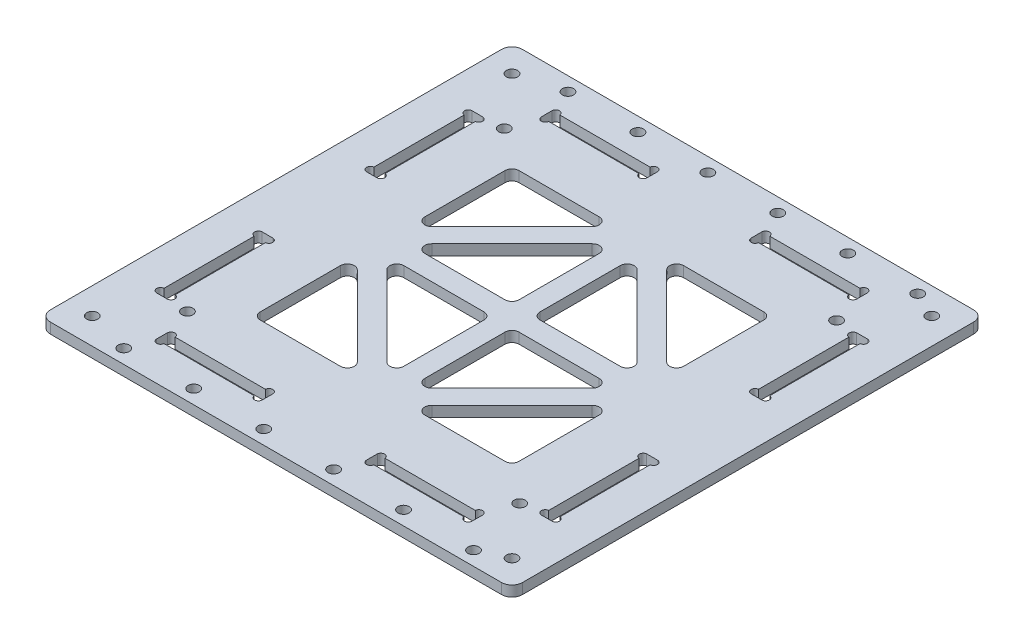
SolidWorks part; units mm, degrees
material "轻木"
ref_plane "Front" through (0, 0, 0) normal (0, 0, 1) x (1, 0, 0)
ref_plane "Top" through (0, 0, 0) normal (0, 1, 0) x (1, 0, 0)
ref_plane "Right" through (0, 0, 0) normal (1, 0, 0) x (0, 0, -1)
sketch "草图1" plane through (0, 0, 0) normal (0, 1, 0) x (1, 0, 0)
  line L1 (-67.5, 67.5) -> (67.5, 67.5)
  line L2 (-67.5, 67.5) -> (-67.5, -67.5)
  line L3 (-67.5, -67.5) -> (67.5, -67.5)
  line L4 (67.5, 67.5) -> (67.5, -67.5)
  line L5 (0, -67.5) -> (0, 67.5) construction
  line L6 (-67.5, 0) -> (67.5, 0) construction
  line L7 (-47.5, -45.3) -> (47.5, -45.3) construction
  line L8 (-47.5, -45.3) -> (-47.5, 45.3) construction
  line L9 (-47.5, 45.3) -> (47.5, 45.3) construction
  line L10 (47.5, -45.3) -> (47.5, 45.3) construction
  line L11 (0, 45.3) -> (0, -45.3) construction
  line L12 (-47.5, 0) -> (47.5, 0) construction
  circle A0 centre (-47.5, 45.3) radius 1.6
  circle A1 centre (47.5, 45.3) radius 1.6
  circle A2 centre (47.5, -45.3) radius 1.6
  circle A3 centre (-47.5, -45.3) radius 1.6
  point P0 (0, 0)
  point P4 (0, 0)
  point P95 (0.9739, 0)
  dimension "D7" = 3.2
  dimension "D1" = 135
  dimension "D2" = 135
  dimension "D3" = 95
  dimension "D4" = 90.6
extrude "凸台-拉伸1" add sketch "草图1" along normal blind 3
sketch "草图2" plane through (0, 3, 0) normal (0, 1, 0) x (1, 0, 0)
  line L0 (-67.5, 55) -> (67.5, 55) construction
  line L1 (-67.5, 67.5) -> (-67.5, -67.5) construction
  line L2 (67.5, -67.5) -> (67.5, 67.5) construction
  line L3 (-67.5, -55) -> (67.5, -55) construction
  line L4 (-45.1, 53.4) -> (-14.9, 53.4)
  line L5 (0, 55) -> (0, -55) construction
  line L6 (-14.9, 53.4) -> (-14.9, 56.6)
  line L7 (-45, 53.5) -> (-15, 53.5)
  line L8 (-45, 53.5) -> (-45, 56.5)
  line L9 (-45, 56.5) -> (-15, 56.5)
  line L10 (-15, 53.5) -> (-15, 56.5)
  line L11 (-30, 56.5) -> (-30, 53.5) construction
  line L12 (-45, 55) -> (-15, 55) construction
  line L13 (-45.1, 56.6) -> (-14.9, 56.6)
  line L14 (-45.1, 53.4) -> (-45.1, 56.6)
  line L15 (-30.1, 56.5) -> (-30.1, 53.5)
  line L16 (-45, 54.9) -> (-15, 54.9)
  circle A0 centre (-16.0003, 56.5) radius 1.0003
  circle A1 centre (-16.0003, 53.5) radius 1.0003
  circle A2 centre (-43.9997, 56.5) radius 1.0003
  circle A3 centre (-43.9997, 53.5) radius 1.0003
  circle A4 centre (-16.0003, 56.5) radius 1.1003
  circle A5 centre (-16.0003, 53.5) radius 1.1003
  circle A6 centre (-43.9997, 56.5) radius 1.1003
  circle A7 centre (-43.9997, 53.5) radius 1.1003
  point P10 (0, 0)
  point P11 (-30, 55)
  dimension "D5" = 2.0006
  dimension "D1" = 110
  dimension "D2" = 30
  dimension "D3" = 30
  dimension "D4" = 3
  dimension "D6" = 0.1
extrude "切除-拉伸1" cut sketch "草图2" against normal blind 10 contours A6 | A7 | L13 L6 L4 L14 | A4 | A5
mirror "镜向1" about plane through (0, 0, 0) normal (1, 0, 0) of "切除-拉伸1"
sketch "草图3" plane through (0, 0, 0) normal (1, 0, 0) x (0, 0, -1)
  line L0 (0, 0) -> (0, 42.0396) construction
pattern_circular "阵列(圆周)1" count 4 over 360 about axis through (0, 0, 0) along (0, 1, 0) of "镜向1", "切除-拉伸1"
sketch "草图4" plane through (0, 3, 0) normal (0, 1, 0) x (1, 0, 0)
  line L1 (-60, -60) -> (60, -60) construction
  line L2 (-60, -60) -> (-60, 60) construction
  line L3 (-60, 60) -> (60, 60) construction
  line L4 (60, -60) -> (60, 60) construction
  line L5 (0, 60) -> (0, -60) construction
  line L6 (-60, 0) -> (60, 0) construction
  circle A0 centre (-60, 60) radius 1.6
  circle A1 centre (60, 60) radius 1.6
  circle A2 centre (60, -60) radius 1.6
  circle A3 centre (-60, -60) radius 1.6
  point P0 (0, 0)
  dimension "D3" = 3.2
  dimension "D1" = 120
  dimension "D2" = 120
extrude "切除-拉伸2" cut sketch "草图4" against normal blind 10
fillet "圆角1" radius 3 4 edges at (67.5, 1.5, 67.5) (-67.5, 1.5, 67.5) (67.5, 1.5, -67.5) (-67.5, 1.5, -67.5)
sketch "草图5" plane through (0, 3, 0) normal (0, 1, 0) x (1, 0, 0)
  line L0 (0, 0) -> (0, 63.9741) construction
  line L1 (0, 0) -> (-90.3045, 0) construction
  line L2 (-7.2426, 37) -> (-37, 37)
  line L3 (0, 0) -> (-40, 0) construction
  line L4 (0, 0) -> (0, 40) construction
  line L5 (0, 40) -> (-40, 40) construction
  line L6 (-40, 0) -> (-40, 40) construction
  line L7 (0, 0) -> (-40, 40) construction
  line L8 (0, 40) -> (-40, 0) construction
  line L9 (-37, 7.2426) -> (-37, 37)
  line L10 (-7.2426, 37) -> (-37, 7.2426)
  line L11 (-3, 32.7574) -> (-32.7574, 3)
  line L12 (-32.7574, 3) -> (-3, 3)
  line L13 (-3, 32.7574) -> (-3, 3)
  line L14 (7.2426, 37) -> (37, 7.2426)
  line L15 (37, 7.2426) -> (37, 37)
  line L16 (7.2426, 37) -> (37, 37)
  line L17 (3, 32.7574) -> (3, 3)
  line L18 (32.7574, 3) -> (3, 3)
  line L19 (3, 32.7574) -> (32.7574, 3)
  line L20 (-7.2426, -37) -> (-37, -7.2426)
  line L21 (-37, -7.2426) -> (-37, -37)
  line L22 (-7.2426, -37) -> (-37, -37)
  line L23 (-3, -32.7574) -> (-3, -3)
  line L24 (-32.7574, -3) -> (-3, -3)
  line L25 (-3, -32.7574) -> (-32.7574, -3)
  line L26 (7.2426, -37) -> (37, -37)
  line L27 (37, -7.2426) -> (37, -37)
  line L28 (7.2426, -37) -> (37, -7.2426)
  line L29 (3, -32.7574) -> (32.7574, -3)
  line L30 (32.7574, -3) -> (3, -3)
  line L31 (3, -32.7574) -> (3, -3)
  point P7 (-20, 20)
  dimension "D1" = 40
  dimension "D2" = 40
  dimension "D3" = 3
extrude "切除-拉伸3" cut sketch "草图5" against normal blind 10
fillet "圆角2" radius 2 24 edges at (3, 1.5, 32.7574) (32.7574, 1.5, 3) (3, 1.5, 3) (7.2426, 1.5, 37) (37, 1.5, 37) (-7.2426, 1.5, 37) (-37, 1.5, 7.2426) (-37, 1.5, 37) (-3, 1.5, 32.7574) (-3, 1.5, 3) (-32.7574, 1.5, 3) (7.2426, 1.5, -37) (37, 1.5, -7.2426) (37, 1.5, -37) (-3, 1.5, -32.7574) (-32.7574, 1.5, -3) (-3, 1.5, -3) (3, 1.5, -32.7574) (3, 1.5, -3) (32.7574, 1.5, -3) (-7.2426, 1.5, -37) (-37, 1.5, -37) (-37, 1.5, -7.2426) (37, 1.5, 7.2426)
sketch "草图6" plane through (0, 0, 0) normal (0, -1, 0) x (1, 0, 0)
  line L0 (67.5, 63.5) -> (-67.5, 63.5) construction
  line L1 (67.5, 64.5) -> (67.5, -64.5) construction
  line L2 (-67.5, -64.5) -> (-67.5, 64.5) construction
  line L3 (-64.5, 67.5) -> (64.5, 67.5) construction
  circle A0 centre (52.5, 63.5) radius 1.6
  circle A1 centre (32.5, 63.5) radius 1.6
  circle A2 centre (12.5, 63.5) radius 1.6
  circle A3 centre (-7.5, 63.5) radius 1.6
  circle A4 centre (-27.5, 63.5) radius 1.6
  circle A5 centre (-47.5, 63.5) radius 1.6
  dimension "D2" = 15
  dimension "D3" = 3.2
  dimension "D1" = 4
  dimension "D4" = 6
extrude "切除-拉伸4" cut sketch "草图6" against normal blind 10
mirror "镜向2" about plane through (0, 0, 0) normal (0, 0, 1) of "切除-拉伸4"
equation "\"8、\"=10"
